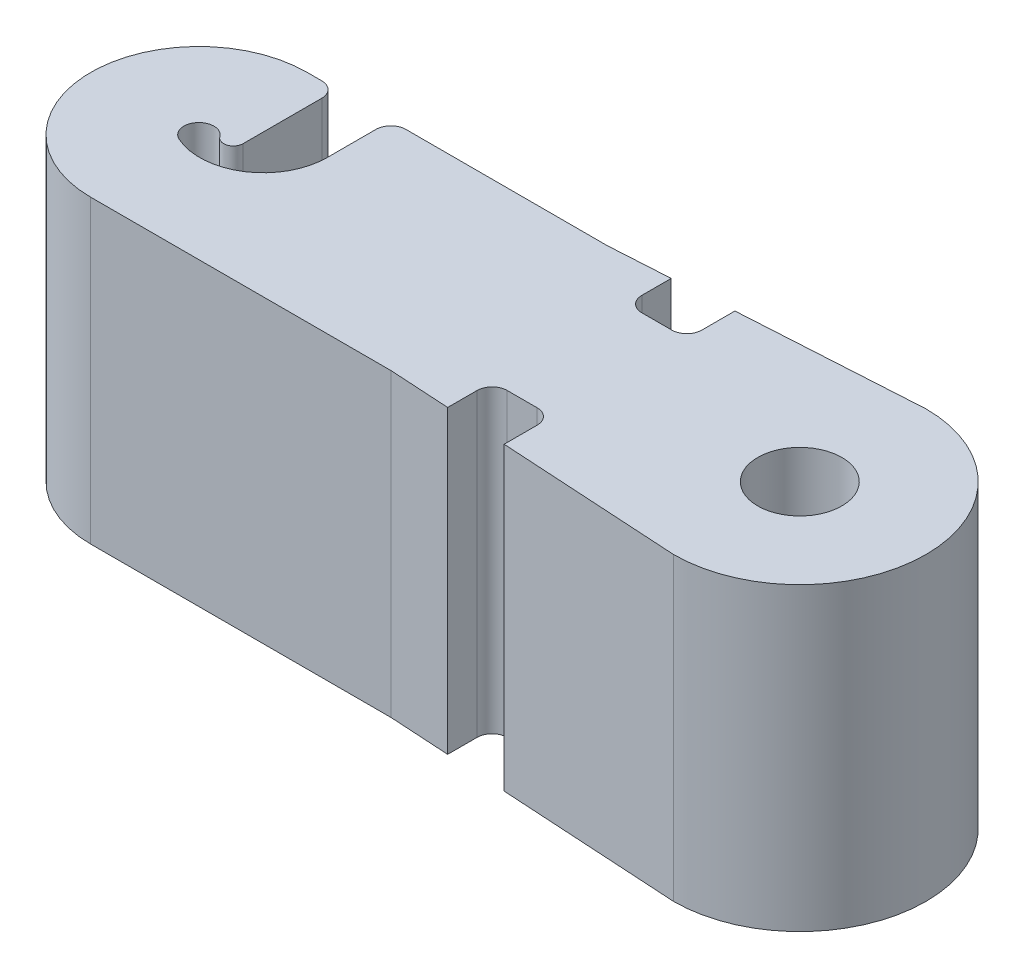
SolidWorks part; units mm, degrees
ref_plane "Front Plane" through (0, 0, 0) normal (0, 0, 1) x (1, 0, 0)
ref_plane "Top Plane" through (0, 0, 0) normal (0, 1, 0) x (1, 0, 0)
ref_plane "Right Plane" through (0, 0, 0) normal (1, 0, 0) x (0, 0, -1)
sketch "Sketch3" plane through (0, 0, 0) normal (0, 1, 0) x (1, 0, 0)
  line L0 (-5, 0.75) -> (0, 1.05) construction
  line L3 (0, -1.05) -> (-5, -0.75) construction
  line L4 (-2.5, 0.9) -> (-2, 0.93)
  line L6 (-4.25, 0) -> (-5.75, 0) construction
  line L7 (-2, 0.93) -> (-2, 0.56)
  line L8 (-2.5, 0.9) -> (-5, 0.9)
  line L9 (-2.5, 0.9) -> (-2.5, -0.9) construction
  line L10 (-2.5, -0.9) -> (-5, -0.9)
  line L11 (-5, 0.9) -> (-5, -0.9) construction
  line L12 (-2, 0.96) -> (-1.5, 0.96) construction
  line L13 (-2, 0.96) -> (-2, 0.56) construction
  line L14 (-2, 0.56) -> (-1.5, 0.56)
  line L15 (-1.5, 0.96) -> (-1.5, 0.56)
  line L16 (-1.5, -0.56) -> (-2, -0.56)
  line L17 (-1.5, -0.56) -> (-1.5, -0.96)
  line L18 (-1.5, -0.96) -> (-2, -0.96) construction
  line L19 (-2, -0.56) -> (-2, -0.96) construction
  line L21 (-2.5, -0.9) -> (-2, -0.93)
  line L22 (-2, -0.93) -> (-2, -0.56)
  line L23 (-1.5, 0.96) -> (0, 1.05)
  line L24 (0, -1.05) -> (-1.5, -0.96)
  circle A2 centre (0, 0) radius 0.6 construction
  circle A3 centre (0, 0) radius 0.4 construction
  circle A4 centre (-5, 0) radius 0.35 construction
  circle A5 centre (0, 0) radius 1.05 construction
  circle A6 centre (-5, 0) radius 0.75 construction
  arc A7 (-5, 0.9) -> (-5, -0.9) centre (-5, 0) ccw
  arc A8 (0, 1.05) -> (0, -1.05) centre (0, 0) cw
  point P4 (-2, -0.93)
  point P15 (-5, 0)
  point P16 (-2, 0.93)
  point P22 (-5, 0)
  dimension "D2" = 1.2
  dimension "D3" = 0.8
  dimension "D4" = 0.7
  dimension "D6" = 5
  dimension "D1" = 1.5
  dimension "D5" = 2.1
  dimension "D7" = 0.4
  dimension "D9" = 2.5
  dimension "D10" = 1.8
  dimension "D11" = 2.5
  dimension "D12" = 0.5
  dimension "D14" = 1.5
extrude "Boss-Extrude1" add sketch "Sketch3" along normal blind 2.5 contours L8 A7 L10 L21 L22 L16 L17 L24 A8 L23 L15 L14 L7 L4
sketch "Sketch4" plane through (0, 2.5, 0) normal (0, 1, 0) x (1, 0, 0)
  line L4 (-4.8724, 0.0389) -> (-4.793, 0.0389) construction
  line L5 (-4.7522, 0.1194) -> (-4.7522, 0.9) construction
  line L7 (-2.5, 0.9) -> (-5, 0.9) construction
  line L8 (-4.7522, 0.9) -> (-4.3022, 0.9)
  line L9 (-4.3022, 0.9) -> (-4.3022, 0.3694)
  line L10 (-4.7522, 0.9) -> (-4.7522, 0.1194)
  line L11 (-4.9363, -0.1611) -> (-4.7291, -0.1611) construction
  line L12 (-4.8327, 0.0389) -> (-4.8327, -0.1611) construction
  circle A0 centre (0, 0) radius 0.35
  circle A1 centre (-5, 0) radius 0.375 construction
  circle A3 centre (-5, 0) radius 0.125 construction
  circle A4 centre (-4.8327, 0.3694) radius 0.5306 construction
  circle A5 centre (-4.8327, 0.1194) radius 0.0806 construction
  arc A6 (-4.7522, 0.1194) -> (-4.8983, 0.0726) centre (-4.8327, 0.1194) cw
  arc A7 (-4.8983, 0.0726) -> (-5.0516, -0.1139) centre (-5, 0) ccw
  arc A8 (-5.0516, -0.1139) -> (-4.3022, 0.3694) centre (-4.8327, 0.3694) ccw
  point P9 (0, 0)
  point P17 (-4.8327, 0.0389)
  point P18 (0, 0)
  point P28 (0, 0)
  point P29 (0, 0)
  point P30 (0, 0)
  point P31 (-4.3022, 0.3694)
  point P32 (0, 0)
  dimension "D1" = 0.7
  dimension "D2" = 0.75
  dimension "D4" = 0.45
  dimension "D3" = 0.25
  dimension "D5" = 0.2
extrude "Through Holes" cut sketch "Sketch4" against normal through all
fillet "Fillet1" radius 0.125 6 edges at (-2, 1.25, 0.56) (-1.5, 1.25, 0.56) (-1.5, 1.25, -0.56) (-2, 1.25, -0.56) (-4.7522, 1.25, -0.9) (-4.3022, 1.25, -0.9)
